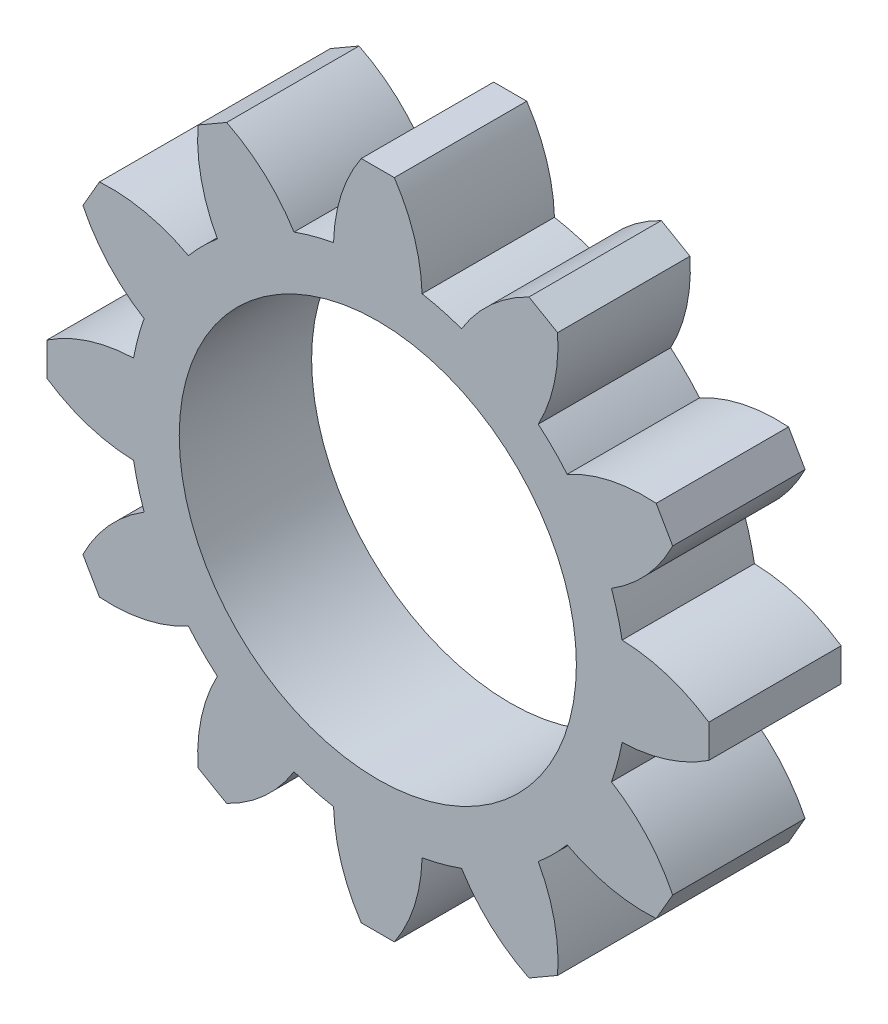
SolidWorks part; units mm, degrees
ref_plane "Front Plane" through (0, 0, 0) normal (1, 0, 0) x (0, 1, 0)
ref_plane "Top Plane" through (0, 0, 0) normal (0, 0, 1) x (0, 1, 0)
ref_plane "Right Plane" through (0, 0, 0) normal (0, 1, 0) x (-1, 0, 0)
sketch "Sketch1" plane through (0, 0, 0) normal (0, 0, 1) x (0, 1, 0)
  line L0 (-28.034, 0) -> (25.5257, 0) construction
  line L1 (14.7596, 2.675) -> (14.7596, -2.675) construction
  line L2 (20, 1) -> (20, -1)
  line L3 (17.8205, -9.134) -> (16.8205, -10.866)
  line L4 (10.866, -16.8205) -> (9.134, -17.8205)
  line L5 (1, -20) -> (-1, -20)
  line L6 (-9.134, -17.8205) -> (-10.866, -16.8205)
  line L7 (-16.8205, -10.866) -> (-17.8205, -9.134)
  line L8 (-20, -1) -> (-20, 1)
  line L9 (-17.8205, 9.134) -> (-16.8205, 10.866)
  line L10 (-10.866, 16.8205) -> (-9.134, 17.8205)
  line L11 (-1, 20) -> (1, 20)
  line L12 (9.134, 17.8205) -> (10.866, 16.8205)
  line L13 (16.8205, 10.866) -> (17.8205, 9.134)
  circle A0 centre (0, 0) radius 12
  arc A1 (14.7596, 2.675) -> (14.1196, 5.0632) centre (0, 0) ccw
  arc A2 (20, 1) -> (14.7596, 2.675) centre (14.5273, -7.0869) ccw
  arc A4 (14.7596, -2.675) -> (20, -1) centre (14.4527, 7.3203) ccw
  arc A5 (17.8205, -9.134) -> (14.1196, -5.0632) centre (9.0375, -13.4011) ccw
  arc A6 (11.4446, -9.6964) -> (16.8205, -10.866) centre (16.1765, -0.8868) ccw
  arc A7 (10.866, -16.8205) -> (9.6964, -11.4446) centre (1.1262, -16.1244) ccw
  arc A8 (5.0632, -14.1196) -> (9.134, -17.8205) centre (13.5659, -8.8562) ccw
  arc A9 (1, -20) -> (2.675, -14.7596) centre (-7.0869, -14.5273) ccw
  arc A10 (-2.675, -14.7596) -> (-1, -20) centre (7.3203, -14.4527) ccw
  arc A11 (-9.134, -17.8205) -> (-5.0632, -14.1196) centre (-13.4011, -9.0375) ccw
  arc A12 (-9.6964, -11.4446) -> (-10.866, -16.8205) centre (-0.8868, -16.1765) ccw
  arc A13 (-16.8205, -10.866) -> (-11.4446, -9.6964) centre (-16.1244, -1.1262) ccw
  arc A14 (-14.1196, -5.0632) -> (-17.8205, -9.134) centre (-8.8562, -13.5659) ccw
  arc A15 (-20, -1) -> (-14.7596, -2.675) centre (-14.5273, 7.0869) ccw
  arc A16 (-14.7596, 2.675) -> (-20, 1) centre (-14.4527, -7.3203) ccw
  arc A17 (-17.8205, 9.134) -> (-14.1196, 5.0632) centre (-9.0375, 13.4011) ccw
  arc A18 (-11.4446, 9.6964) -> (-16.8205, 10.866) centre (-16.1765, 0.8868) ccw
  arc A19 (-10.866, 16.8205) -> (-9.6964, 11.4446) centre (-1.1262, 16.1244) ccw
  arc A20 (-5.0632, 14.1196) -> (-9.134, 17.8205) centre (-13.5659, 8.8562) ccw
  arc A21 (-1, 20) -> (-2.675, 14.7596) centre (7.0869, 14.5273) ccw
  arc A22 (2.675, 14.7596) -> (1, 20) centre (-7.3203, 14.4527) ccw
  arc A23 (9.134, 17.8205) -> (5.0632, 14.1196) centre (13.4011, 9.0375) ccw
  arc A24 (9.6964, 11.4446) -> (10.866, 16.8205) centre (0.8868, 16.1765) ccw
  arc A25 (16.8205, 10.866) -> (11.4446, 9.6964) centre (16.1244, 1.1262) ccw
  arc A26 (14.1196, 5.0632) -> (17.8205, 9.134) centre (8.8562, 13.5659) ccw
  arc A27 (11.4446, 9.6964) -> (9.6964, 11.4446) centre (0, 0) ccw
  arc A28 (5.0632, 14.1196) -> (2.675, 14.7596) centre (0, 0) ccw
  arc A29 (-2.675, 14.7596) -> (-5.0632, 14.1196) centre (0, 0) ccw
  arc A30 (-9.6964, 11.4446) -> (-11.4446, 9.6964) centre (0, 0) ccw
  arc A31 (-14.1196, 5.0632) -> (-14.7596, 2.675) centre (0, 0) ccw
  arc A32 (-14.7596, -2.675) -> (-14.1196, -5.0632) centre (0, 0) ccw
  arc A33 (-11.4446, -9.6964) -> (-9.6964, -11.4446) centre (0, 0) ccw
  arc A34 (-5.0632, -14.1196) -> (-2.675, -14.7596) centre (0, 0) ccw
  arc A35 (2.675, -14.7596) -> (5.0632, -14.1196) centre (0, 0) ccw
  arc A36 (9.6964, -11.4446) -> (11.4446, -9.6964) centre (0, 0) ccw
  arc A37 (14.1196, -5.0632) -> (14.7596, -2.675) centre (0, 0) ccw
  point P12 (20, 0)
  point P82 (0, 0)
  dimension "D1" = 24
  dimension "D2" = 30
  dimension "D7" = 12
  dimension "D8" = 9.7647
  dimension "D9" = 10
  dimension "D3" = 20
  dimension "D4" = 1
  dimension "D5" = 1
  dimension "D6" = 5.35
extrude "Boss-Extrude1" add sketch "Sketch1" along normal blind 8
